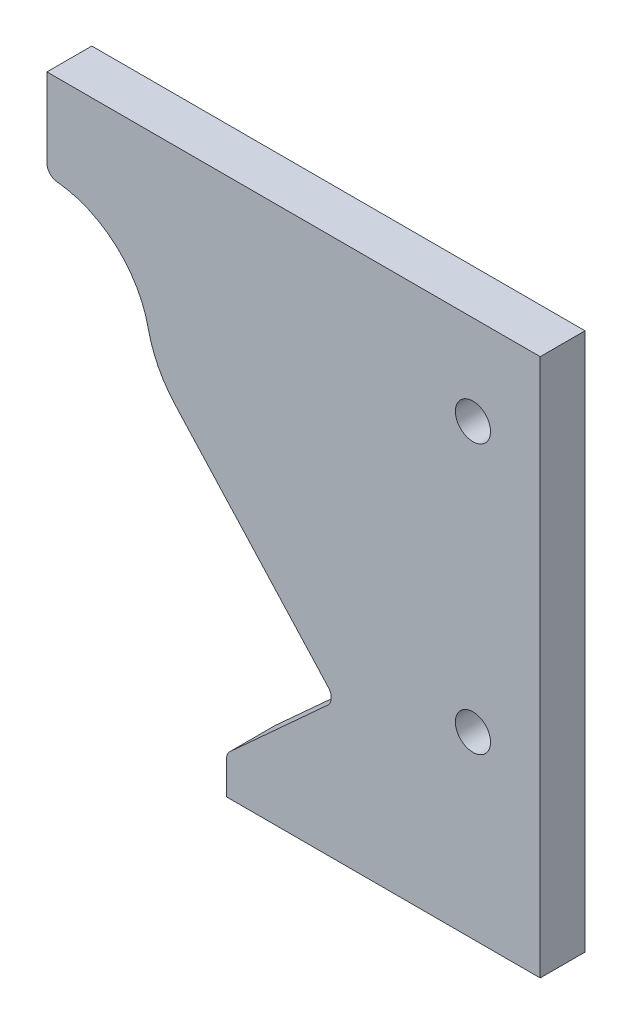
SolidWorks part; units mm, degrees
material "6061 Alloy"
ref_plane "X-Y Datum" through (0, 0, 0) normal (0, 0, 1) x (1, 0, 0)
ref_plane "X-Z Datum" through (0, 0, 0) normal (0, 1, 0) x (1, 0, 0)
ref_plane "Y-Z Datum" through (0, 0, 0) normal (1, 0, 0) x (0, 0, -1)
sketch "Sketch1" plane through (0, 0, 0) normal (0, 0, 1) x (1, 0, 0)
  line L0 (0, 27.3812) -> (69.85, 27.3812)
  line L3 (0, 27.3812) -> (0, 14.6812)
  line L10 (69.85, 27.3812) -> (69.85, -48.8188)
  line L16 (69.85, -48.8188) -> (25.426, -48.8188)
  line L21 (25.426, -43.4598) -> (40.9152, -29.346)
  line L22 (40.9152, -29.346) -> (18.162, -4.3757)
  line L23 (25.426, -48.8188) -> (25.426, -43.4598)
  circle A8 centre (60.325, -23.4188) radius 2.4892
  circle A9 centre (60.325, 14.6812) radius 2.4892
  arc A15 (14.3641, 3.0349) -> (0, 14.6812) centre (0, 0) ccw
  arc A16 (18.162, -4.3757) -> (14.3641, 3.0349) centre (29.8962, 6.3166) cw
  point P19 (0, 14.6812)
  point P25 (38.6617, -32.257)
  dimension "D1" = 12.7
  dimension "D4" = 20.955
  dimension "D8" = 15.875
  dimension "D10" = 4.9784
  dimension "D18" = 14.6812
  dimension "D7" = 69.85
  dimension "D9" = 76.2
  dimension "D11" = 25.4
  dimension "D12" = 9.525
  dimension "D13" = 12.7
  dimension "D16" = 9.525
extrude "Boss-Extrude1" add sketch "Sketch1" along normal mid plane 6.35
fillet "Fillet1" radius 1.5875 3 edges at (0, 14.6812, 0) (40.9152, -29.346, 0) (25.426, -43.4598, 0)
